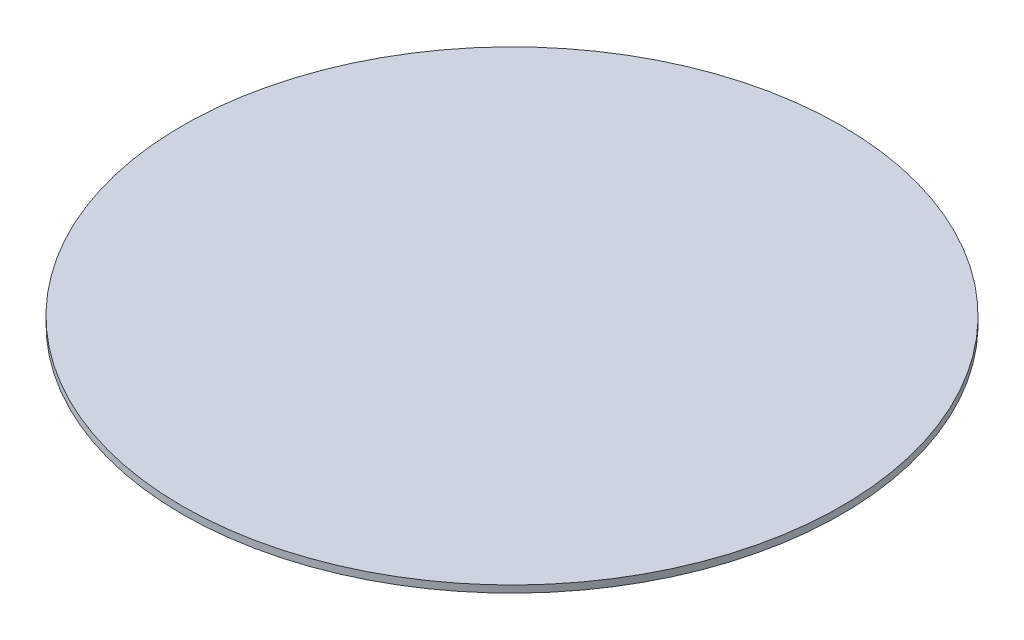
SolidWorks part; units mm, degrees
ref_plane "Front Plane" through (0, 0, 0) normal (0, 0, 1) x (1, 0, 0)
ref_plane "Top Plane" through (0, 0, 0) normal (0, 1, 0) x (1, 0, 0)
ref_plane "Right Plane" through (0, 0, 0) normal (1, 0, 0) x (0, 0, -1)
sketch "Sketch1" plane through (0, 0, 0) normal (0, 1, 0) x (1, 0, 0)
  circle A0 centre (0, 0) radius 140
  dimension "D1" = 280
extrude "Boss-Extrude1" add sketch "Sketch1" along normal blind 3
